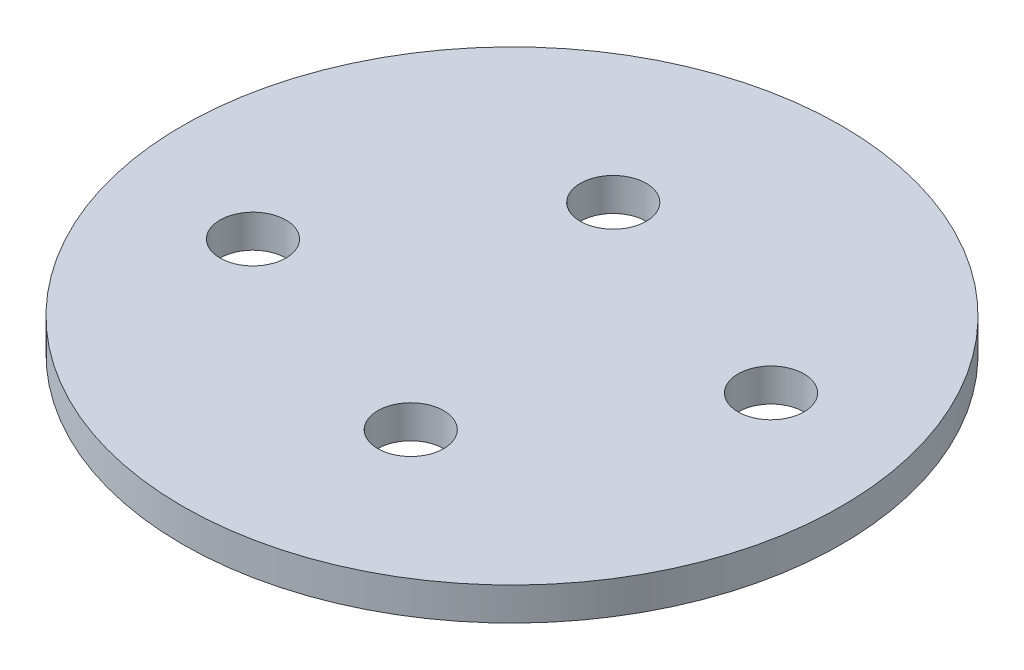
SolidWorks part; units mm, degrees
ref_plane "Front Plane" through (0, 0, 0) normal (0, 0, 1) x (1, 0, 0)
ref_plane "Top Plane" through (0, 0, 0) normal (0, 1, 0) x (1, 0, 0)
ref_plane "Right Plane" through (0, 0, 0) normal (1, 0, 0) x (0, 0, -1)
sketch "Sketch2" plane through (0, 0, 0) normal (0, 1, 0) x (1, 0, 0)
  line L0 (-72.4784, 40.6586) -> (-40.6586, 72.4784)
  line L5 (-80, -80) -> (80, -80)
  line L6 (-80, -80) -> (-80, 80)
  line L7 (-80, 80) -> (80, 80)
  line L8 (80, -80) -> (80, 80)
  line L9 (0, -55) -> (0, 55) construction
  line L10 (-80, -80) -> (80, 80) construction
  line L11 (-80, 80) -> (80, -80) construction
  line L12 (-72.4784, 40.6586) -> (-213.8998, 182.08)
  line L13 (-40.6586, 72.4784) -> (-182.08, 213.8998)
  line L14 (-213.8998, 182.08) -> (-182.08, 213.8998)
  line L15 (40.6586, 72.4784) -> (182.08, 213.8998)
  line L16 (213.8998, 182.08) -> (182.08, 213.8998)
  line L17 (72.4784, 40.6586) -> (213.8998, 182.08)
  line L18 (72.4784, 40.6586) -> (40.6586, 72.4784)
  line L19 (-80, 0) -> (80, 0) construction
  line L20 (72.4784, -40.6586) -> (40.6586, -72.4784)
  line L21 (72.4784, -40.6586) -> (213.8998, -182.08)
  line L22 (213.8998, -182.08) -> (182.08, -213.8998)
  line L23 (40.6586, -72.4784) -> (182.08, -213.8998)
  line L24 (-40.6586, -72.4784) -> (-182.08, -213.8998)
  line L25 (-213.8998, -182.08) -> (-182.08, -213.8998)
  line L26 (-72.4784, -40.6586) -> (-213.8998, -182.08)
  line L27 (-72.4784, -40.6586) -> (-40.6586, -72.4784)
  line L28 (-197.9899, 197.9899) -> (197.9899, -197.9899) construction
  line L29 (0, 0) -> (0, -64.6157) construction
  line L30 (-55, 0) -> (55, 0) construction
  circle A0 centre (-197.9899, 197.9899) radius 152.4
  circle A1 centre (197.9899, 197.9899) radius 152.4
  circle A2 centre (197.9899, -197.9899) radius 152.4
  circle A3 centre (-197.9899, -197.9899) radius 152.4
  circle A5 centre (-197.9899, 197.9899) radius 20
  circle A6 centre (-197.9899, 197.9899) radius 150
  circle A7 centre (197.9899, 197.9899) radius 150
  circle A8 centre (197.9899, 197.9899) radius 20
  circle A9 centre (197.9899, -197.9899) radius 20
  circle A10 centre (197.9899, -197.9899) radius 150
  circle A11 centre (-197.9899, -197.9899) radius 20
  circle A12 centre (-197.9899, -197.9899) radius 150
  circle A13 centre (195.089, -188.9436) radius 2
  circle A14 centre (209.8929, -194.1729) radius 2
  circle A15 centre (200.8908, -207.0362) radius 2
  circle A16 centre (186.0869, -201.8069) radius 2
  point P0 (0, 0)
  point P7 (-56.5685, 56.5685)
  dimension "D4" = 80
  dimension "D6" = 304.8
  dimension "D7" = 40
  dimension "D8" = 300
  dimension "D9" = 4
  dimension "D10" = 4
  dimension "D11" = 4
  dimension "D12" = 4
  dimension "D1" = 160
  dimension "D2" = 200
  dimension "D3" = 45
  dimension "D5" = 45
extrude "Boss-Extrude1" add sketch "Sketch2" along normal blind 2 contours L22 A9 A16 A13 | L22 A9 A15 A14 | A0 | A2 | A3 | A1 | L12 L14 L13 L0 | A11 | L24 L25 L26 L27 | L17 L16 L15 L18 | L7 L8 L5 L6
ref_plane "Plane4" through (0, 0, 0) normal (0, 0, -1) x (-1, 0, 0)
ref_plane "Plane5" through (0, 0, -25) normal (0, 0, -1) x (-1, 0, 0)
ref_plane "Plane6" through (0, 0, 25) normal (0, 0, -1) x (-1, 0, 0)
